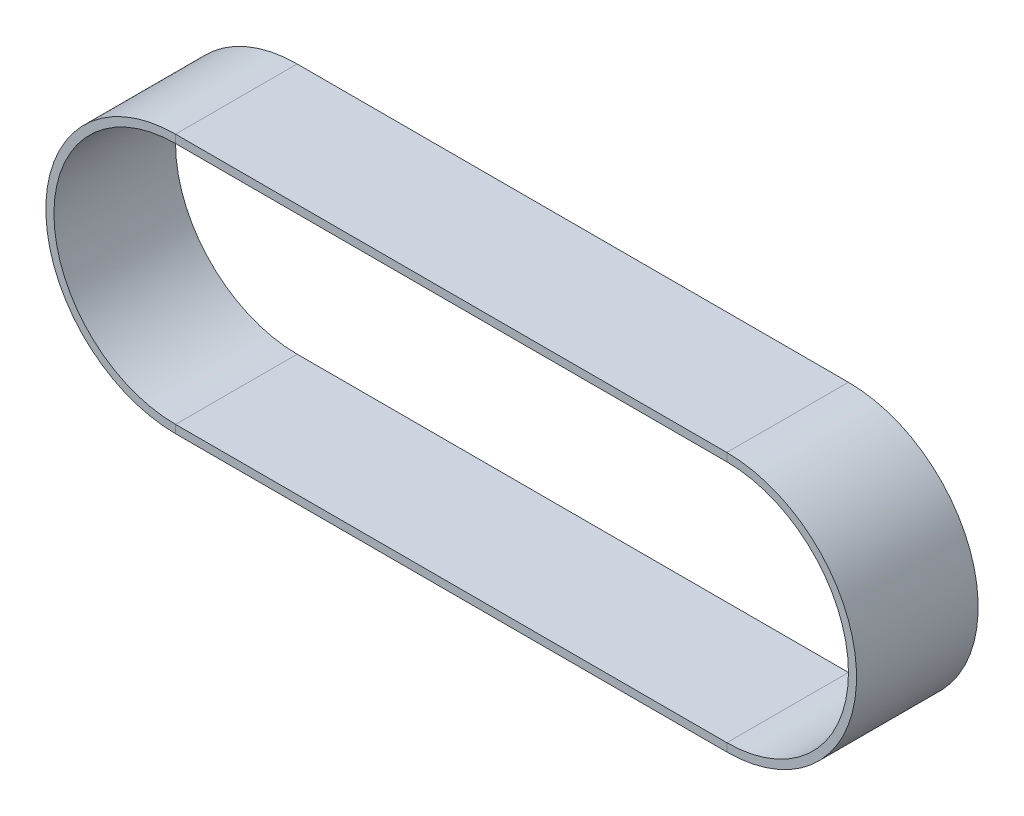
SolidWorks part; units mm, degrees
material "EPDM 60 Durometer"
ref_plane "Ebene vorne" through (0, 0, 0) normal (0, 0, 1) x (1, 0, 0)
ref_plane "Ebene oben" through (0, 0, 0) normal (0, 1, 0) x (1, 0, 0)
ref_plane "Ebene rechts" through (0, 0, 0) normal (1, 0, 0) x (0, 0, -1)
sketch "Skizze2" plane through (0, 0, 0) normal (0, 0, 1) x (1, 0, 0)
  line L0 (0, 0) -> (1, 0) construction
  line L1 (0, 0) -> (0, 1) construction
  line L2 (2, -300) -> (-1358, -300)
  line L3 (-1358, 300) -> (2, 300)
  arc A0 (2, 300) -> (2, -300) centre (2, 0) cw
  arc A1 (-1358, -300) -> (-1358, 300) centre (-1358, 0) cw
sketch3d "3D-Skizze2"
  line L0 (-1358, 300, 0) -> (2, 300, 0) construction
  line L2 (2, 320, -150) -> (2, 320, 150)
  line L3 (2, 320, -150) -> (2, 300, -150)
  line L4 (2, 300, -150) -> (2, 300, 150)
  line L5 (2, 320, 150) -> (2, 300, 150)
  point P7 (2, 300, 0)
  dimension "D1" = 300
  dimension "D2" = 20
sweep "Austragung1" add profiles "3D-Skizze2" path "Skizze2"
